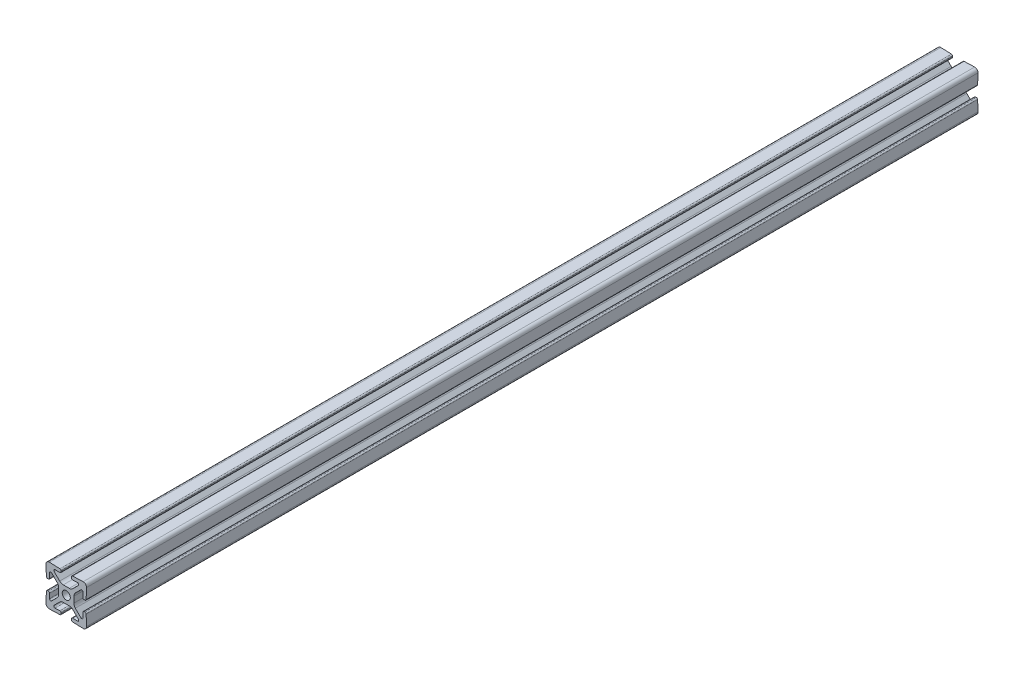
SolidWorks part; units mm, degrees
ref_plane "Front Plane" through (0, 0, 0) normal (0, 0, 1) x (1, 0, 0)
ref_plane "Top Plane" through (0, 0, 0) normal (0, 1, 0) x (1, 0, 0)
ref_plane "Right Plane" through (0, 0, 0) normal (1, 0, 0) x (0, 0, -1)
sketch "Sketch1" plane through (0, 0, 0) normal (0, 0, 1) x (1, 0, 0)
  line L0 (0, 0) -> (0, 12.7) construction
  line L1 (0, 0) -> (12.7, 0) construction
  line L2 (0, 0) -> (-12.7, 12.7) construction
  line L3 (-10.5971, 12.6988) -> (-3.9739, 12.4675)
  line L4 (-12.7, 12.7) -> (0, 12.7) construction
  line L6 (-4.0475, 10.3606) -> (-7.0332, 10.4648)
  line L10 (0, 4.7625) -> (-1.8848, 4.7625)
  line L11 (-4.1299, 5.6924) -> (-7.5996, 9.1622)
  line L24 (0, 0) -> (-12.7, 0) construction
  line L25 (-12.7, 0) -> (0, 0) construction
  line L26 (0, 0) -> (0, -12.7) construction
  line L27 (-12.7, -12.7) -> (-12.7, 12.7) construction
  line L28 (0, 12.7) -> (12.7, 12.7) construction
  line L29 (-3.239, 11.6793) -> (-3.2594, 11.0955)
  line L30 (-12.7, -12.7) -> (12.7, -12.7) construction
  arc A0 (-12.1048, 12.1048) -> (-10.5971, 12.6988) centre (-10.668, 10.668) cw
  arc A6 (-1.8848, 4.7625) -> (-4.1299, 5.6924) centre (-1.8848, 7.9375) cw
  circle A16 centre (0, 0) radius 2.54
  arc A18 (-7.5996, 9.1622) -> (-7.0332, 10.4648) centre (-7.0599, 9.702) cw
  circle A19 centre (-2.3794, 2.3794) radius 0.635 construction
  arc A20 (-4.0475, 10.3606) -> (-3.2594, 11.0955) centre (-4.0209, 11.1221) ccw
  arc A21 (-3.9739, 12.4675) -> (-3.239, 11.6793) centre (-4.0005, 11.7059) cw
  point P15 (0, 0)
  point P42 (-3.1999, 4.7625)
  point P80 (-12.7, 0)
  point P85 (0, -12.7)
  point P88 (0, -12.7)
  dimension "D11" = 2.032
  dimension "D15" = 3.175
  dimension "Center Hole Diameter" = 5.08
  dimension "D6" = 1.27
  dimension "D4" = 0.7633
  dimension "D8" = 0.762
  dimension "D12" = 0.762
  dimension "D1" = 45
  dimension "D2" = 2
  dimension "Rail Width" = 25.4
  dimension "D10" = 2.2098
  dimension "T-Slot Depth" = 7.9375
  dimension "D9" = 2.1082
  dimension "Rail Height" = 25.4
  dimension "D23" = 9.525
  dimension "D5" = 15.6464
  dimension "D3" = 4
  dimension "D7" = 5.7028
  dimension "T-Slot Width" = 6.477
sketch "Sketch2" plane through (0, 0, 0) normal (1, 0, 0) x (0, 0, -1)
  line L0 (-609.6, 0) -> (609.6, 0)
  line L2 (0, 0) -> (0, 12.7) construction
  line L3 (0, 0) -> (0, 12.7) construction
  point P0 (-571.5, 0)
  point P3 (0, 0)
  point P7 (571.5, 0)
  dimension "D1" = 38.1
  dimension "Length" = 1219.2
sketch "Sketch3" plane through (0, 0, 0) normal (0, 0, 1) x (1, 0, 0)
  line L2 (0, 4.7625) -> (-1.8848, 4.7625) construction
  line L5 (-4.1299, 5.6924) -> (-7.5996, 9.1622) construction
  line L6 (-4.0475, 10.3606) -> (-7.0332, 10.4648) construction
  line L7 (-3.239, 11.6793) -> (-3.2594, 11.0955) construction
  line L67 (-10.5971, 12.6988) -> (-3.9739, 12.4675) construction
  line L68 (0, 4.7625) -> (-1.8848, 4.7625)
  line L69 (-4.1299, 5.6924) -> (-7.5996, 9.1622)
  line L70 (-4.0475, 10.3606) -> (-7.0332, 10.4648)
  line L71 (-3.239, 11.6793) -> (-3.2594, 11.0955)
  line L72 (-10.5971, 12.6988) -> (-3.9739, 12.4675)
  line L73 (0, 0) -> (-12.7, 12.7) construction
  line L74 (0, 0) -> (-12.7, 12.7) construction
  line L75 (-12.6988, 10.5971) -> (-12.4675, 3.9739)
  line L76 (-11.6793, 3.239) -> (-11.0955, 3.2594)
  line L77 (-10.3606, 4.0475) -> (-10.4648, 7.0332)
  line L78 (-5.6924, 4.1299) -> (-9.1622, 7.5996)
  line L79 (-4.7625, 0) -> (-4.7625, 1.8848)
  line L80 (-4.7625, 0) -> (-2.54, 0)
  line L82 (0, 4.7625) -> (0, 2.54)
  arc A3 (-4.1299, 5.6924) -> (-1.8848, 4.7625) centre (-1.8848, 7.9375) ccw construction
  circle A10 centre (0, 0) radius 2.54
  arc A56 (0, 2.54) -> (-2.54, 0) centre (0, 0) ccw
  arc A57 (-7.0332, 10.4648) -> (-7.5996, 9.1622) centre (-7.0599, 9.702) ccw construction
  arc A58 (-4.0475, 10.3606) -> (-3.2594, 11.0955) centre (-4.0209, 11.1221) ccw construction
  arc A59 (-3.239, 11.6793) -> (-3.9739, 12.4675) centre (-4.0005, 11.7059) ccw construction
  arc A60 (-10.5971, 12.6988) -> (-12.1048, 12.1048) centre (-10.668, 10.668) ccw construction
  arc A61 (-4.1299, 5.6924) -> (-1.8848, 4.7625) centre (-1.8848, 7.9375) ccw
  arc A62 (-7.0332, 10.4648) -> (-7.5996, 9.1622) centre (-7.0599, 9.702) ccw
  arc A63 (-4.0475, 10.3606) -> (-3.2594, 11.0955) centre (-4.0209, 11.1221) ccw
  arc A64 (-3.239, 11.6793) -> (-3.9739, 12.4675) centre (-4.0005, 11.7059) ccw
  arc A65 (-10.5971, 12.6988) -> (-12.6988, 10.5971) centre (-10.668, 10.668) ccw
  arc A67 (-11.6793, 3.239) -> (-12.4675, 3.9739) centre (-11.7059, 4.0005) cw
  arc A68 (-10.3606, 4.0475) -> (-11.0955, 3.2594) centre (-11.1221, 4.0209) cw
  arc A69 (-10.4648, 7.0332) -> (-9.1622, 7.5996) centre (-9.702, 7.0599) cw
  arc A70 (-5.6924, 4.1299) -> (-4.7625, 1.8848) centre (-7.9375, 1.8848) cw
  dimension "D1" = 0
extrude "Boss-Extrude1" add sketch "Sketch3" along normal mid plane 1219.2
pattern_circular "CirPattern1" count 4 over 360 about axis through (0, 0, 0) along (0, 0, 1) of "Boss-Extrude1"
ref_plane "Contact Plane 1" through (0, 12.7, 0) normal (0, 1, 0) x (1, 0, 0)
ref_plane "Contact Plane 2" through (12.7, 0, 0) normal (1, 0, 0) x (0, 0, -1)
ref_plane "Contact Plane 3" through (0, -12.7, 0) normal (0, -1, 0) x (-1, 0, 0)
ref_plane "Contact Plane 4" through (-12.7, 0, 0) normal (-1, 0, 0) x (0, 0, 1)
sketch "Sketch4" plane through (0, 0, 609.6) normal (0, 0, 1) x (1, 0, 0)
  line L36 (1.8848, 4.7625) -> (-1.8848, 4.7625)
  line L37 (-4.1299, 5.6924) -> (-7.5996, 9.1622)
  line L38 (-7.0332, 10.4648) -> (-4.0475, 10.3606)
  line L39 (-3.2594, 11.0955) -> (-3.239, 11.6793)
  line L40 (-3.9739, 12.4675) -> (-10.5971, 12.6988)
  line L41 (-12.6988, 10.5971) -> (-12.4675, 3.9739)
  line L42 (-11.6793, 3.239) -> (-11.0955, 3.2594)
  line L43 (-10.3606, 4.0475) -> (-10.4648, 7.0332)
  line L44 (-9.1622, 7.5996) -> (-5.6924, 4.1299)
  line L45 (-4.7625, 1.8848) -> (-4.7625, -1.8848)
  line L46 (-5.6924, -4.1299) -> (-9.1622, -7.5996)
  line L47 (-10.4648, -7.0332) -> (-10.3606, -4.0475)
  line L48 (-11.0955, -3.2594) -> (-11.6793, -3.239)
  line L49 (-12.4675, -3.9739) -> (-12.6988, -10.5971)
  line L50 (-10.5971, -12.6988) -> (-3.9739, -12.4675)
  line L51 (-3.239, -11.6793) -> (-3.2594, -11.0955)
  line L52 (-4.0475, -10.3606) -> (-7.0332, -10.4648)
  line L53 (-7.5996, -9.1622) -> (-4.1299, -5.6924)
  line L54 (-1.8848, -4.7625) -> (1.8848, -4.7625)
  line L55 (4.1299, -5.6924) -> (7.5996, -9.1622)
  line L56 (7.0332, -10.4648) -> (4.0475, -10.3606)
  line L57 (3.2594, -11.0955) -> (3.239, -11.6793)
  line L58 (3.9739, -12.4675) -> (10.5971, -12.6988)
  line L59 (12.6988, -10.5971) -> (12.4675, -3.9739)
  line L60 (11.6793, -3.239) -> (11.0955, -3.2594)
  line L61 (10.3606, -4.0475) -> (10.4648, -7.0332)
  line L62 (9.1622, -7.5996) -> (5.6924, -4.1299)
  line L63 (4.7625, -1.8848) -> (4.7625, 1.8848)
  line L64 (5.6924, 4.1299) -> (9.1622, 7.5996)
  line L65 (10.4648, 7.0332) -> (10.3606, 4.0475)
  line L66 (11.0955, 3.2594) -> (11.6793, 3.239)
  line L67 (12.4675, 3.9739) -> (12.6988, 10.5971)
  line L68 (10.5971, 12.6988) -> (3.9739, 12.4675)
  line L69 (3.239, 11.6793) -> (3.2594, 11.0955)
  line L70 (4.0475, 10.3606) -> (7.0332, 10.4648)
  line L71 (7.5996, 9.1622) -> (4.1299, 5.6924)
  line L72 (1.8848, 4.7625) -> (-1.8848, 4.7625)
  line L73 (-4.1299, 5.6924) -> (-7.5996, 9.1622)
  line L74 (-7.0332, 10.4648) -> (-4.0475, 10.3606)
  line L75 (-3.2594, 11.0955) -> (-3.239, 11.6793)
  line L76 (-3.9739, 12.4675) -> (-10.5971, 12.6988)
  line L77 (-12.6988, 10.5971) -> (-12.4675, 3.9739)
  line L78 (-11.6793, 3.239) -> (-11.0955, 3.2594)
  line L79 (-10.3606, 4.0475) -> (-10.4648, 7.0332)
  line L80 (-9.1622, 7.5996) -> (-5.6924, 4.1299)
  line L81 (-4.7625, 1.8848) -> (-4.7625, -1.8848)
  line L82 (-5.6924, -4.1299) -> (-9.1622, -7.5996)
  line L83 (-10.4648, -7.0332) -> (-10.3606, -4.0475)
  line L84 (-11.0955, -3.2594) -> (-11.6793, -3.239)
  line L85 (-12.4675, -3.9739) -> (-12.6988, -10.5971)
  line L86 (-10.5971, -12.6988) -> (-3.9739, -12.4675)
  line L87 (-3.239, -11.6793) -> (-3.2594, -11.0955)
  line L88 (-4.0475, -10.3606) -> (-7.0332, -10.4648)
  line L89 (-7.5996, -9.1622) -> (-4.1299, -5.6924)
  line L90 (-1.8848, -4.7625) -> (1.8848, -4.7625)
  line L91 (4.1299, -5.6924) -> (7.5996, -9.1622)
  line L92 (7.0332, -10.4648) -> (4.0475, -10.3606)
  line L93 (3.2594, -11.0955) -> (3.239, -11.6793)
  line L94 (3.9739, -12.4675) -> (10.5971, -12.6988)
  line L95 (12.6988, -10.5971) -> (12.4675, -3.9739)
  line L96 (11.6793, -3.239) -> (11.0955, -3.2594)
  line L97 (10.3606, -4.0475) -> (10.4648, -7.0332)
  line L98 (9.1622, -7.5996) -> (5.6924, -4.1299)
  line L99 (4.7625, -1.8848) -> (4.7625, 1.8848)
  line L100 (5.6924, 4.1299) -> (9.1622, 7.5996)
  line L101 (10.4648, 7.0332) -> (10.3606, 4.0475)
  line L102 (11.0955, 3.2594) -> (11.6793, 3.239)
  line L103 (12.4675, 3.9739) -> (12.6988, 10.5971)
  line L104 (10.5971, 12.6988) -> (3.9739, 12.4675)
  line L105 (3.239, 11.6793) -> (3.2594, 11.0955)
  line L106 (4.0475, 10.3606) -> (7.0332, 10.4648)
  line L107 (7.5996, 9.1622) -> (4.1299, 5.6924)
  arc A36 (1.8848, 4.7625) -> (4.1299, 5.6924) centre (1.8848, 7.9375) ccw
  arc A37 (-4.1299, 5.6924) -> (-1.8848, 4.7625) centre (-1.8848, 7.9375) ccw
  arc A38 (-7.0332, 10.4648) -> (-7.5996, 9.1622) centre (-7.0599, 9.702) ccw
  arc A39 (-4.0475, 10.3606) -> (-3.2594, 11.0955) centre (-4.0209, 11.1221) ccw
  arc A40 (-3.239, 11.6793) -> (-3.9739, 12.4675) centre (-4.0005, 11.7059) ccw
  arc A41 (-10.5971, 12.6988) -> (-12.6988, 10.5971) centre (-10.668, 10.668) ccw
  arc A42 (-12.4675, 3.9739) -> (-11.6793, 3.239) centre (-11.7059, 4.0005) ccw
  arc A43 (-11.0955, 3.2594) -> (-10.3606, 4.0475) centre (-11.1221, 4.0209) ccw
  arc A44 (-9.1622, 7.5996) -> (-10.4648, 7.0332) centre (-9.702, 7.0599) ccw
  arc A45 (-4.7625, 1.8848) -> (-5.6924, 4.1299) centre (-7.9375, 1.8848) ccw
  arc A46 (-5.6924, -4.1299) -> (-4.7625, -1.8848) centre (-7.9375, -1.8848) ccw
  arc A47 (-10.4648, -7.0332) -> (-9.1622, -7.5996) centre (-9.702, -7.0599) ccw
  arc A48 (-10.3606, -4.0475) -> (-11.0955, -3.2594) centre (-11.1221, -4.0209) ccw
  arc A49 (-11.6793, -3.239) -> (-12.4675, -3.9739) centre (-11.7059, -4.0005) ccw
  arc A50 (-12.6988, -10.5971) -> (-10.5971, -12.6988) centre (-10.668, -10.668) ccw
  arc A51 (-3.9739, -12.4675) -> (-3.239, -11.6793) centre (-4.0005, -11.7059) ccw
  arc A52 (-3.2594, -11.0955) -> (-4.0475, -10.3606) centre (-4.0209, -11.1221) ccw
  arc A53 (-7.5996, -9.1622) -> (-7.0332, -10.4648) centre (-7.0599, -9.702) ccw
  arc A54 (-1.8848, -4.7625) -> (-4.1299, -5.6924) centre (-1.8848, -7.9375) ccw
  arc A55 (4.1299, -5.6924) -> (1.8848, -4.7625) centre (1.8848, -7.9375) ccw
  arc A56 (7.0332, -10.4648) -> (7.5996, -9.1622) centre (7.0599, -9.702) ccw
  arc A57 (4.0475, -10.3606) -> (3.2594, -11.0955) centre (4.0209, -11.1221) ccw
  arc A58 (3.239, -11.6793) -> (3.9739, -12.4675) centre (4.0005, -11.7059) ccw
  arc A59 (10.5971, -12.6988) -> (12.6988, -10.5971) centre (10.668, -10.668) ccw
  arc A60 (12.4675, -3.9739) -> (11.6793, -3.239) centre (11.7059, -4.0005) ccw
  arc A61 (11.0955, -3.2594) -> (10.3606, -4.0475) centre (11.1221, -4.0209) ccw
  arc A62 (9.1622, -7.5996) -> (10.4648, -7.0332) centre (9.702, -7.0599) ccw
  arc A63 (4.7625, -1.8848) -> (5.6924, -4.1299) centre (7.9375, -1.8848) ccw
  arc A64 (5.6924, 4.1299) -> (4.7625, 1.8848) centre (7.9375, 1.8848) ccw
  arc A65 (10.4648, 7.0332) -> (9.1622, 7.5996) centre (9.702, 7.0599) ccw
  arc A66 (10.3606, 4.0475) -> (11.0955, 3.2594) centre (11.1221, 4.0209) ccw
  arc A67 (11.6793, 3.239) -> (12.4675, 3.9739) centre (11.7059, 4.0005) ccw
  arc A68 (12.6988, 10.5971) -> (10.5971, 12.6988) centre (10.668, 10.668) ccw
  arc A69 (3.9739, 12.4675) -> (3.239, 11.6793) centre (4.0005, 11.7059) ccw
  arc A70 (3.2594, 11.0955) -> (4.0475, 10.3606) centre (4.0209, 11.1221) ccw
  arc A71 (7.5996, 9.1622) -> (7.0332, 10.4648) centre (7.0599, 9.702) ccw
  arc A72 (1.8848, 4.7625) -> (4.1299, 5.6924) centre (1.8848, 7.9375) ccw
  arc A73 (-4.1299, 5.6924) -> (-1.8848, 4.7625) centre (-1.8848, 7.9375) ccw
  arc A74 (-7.0332, 10.4648) -> (-7.5996, 9.1622) centre (-7.0599, 9.702) ccw
  arc A75 (-4.0475, 10.3606) -> (-3.2594, 11.0955) centre (-4.0209, 11.1221) ccw
  arc A76 (-3.239, 11.6793) -> (-3.9739, 12.4675) centre (-4.0005, 11.7059) ccw
  arc A77 (-10.5971, 12.6988) -> (-12.6988, 10.5971) centre (-10.668, 10.668) ccw
  arc A78 (-12.4675, 3.9739) -> (-11.6793, 3.239) centre (-11.7059, 4.0005) ccw
  arc A79 (-11.0955, 3.2594) -> (-10.3606, 4.0475) centre (-11.1221, 4.0209) ccw
  arc A80 (-9.1622, 7.5996) -> (-10.4648, 7.0332) centre (-9.702, 7.0599) ccw
  arc A81 (-4.7625, 1.8848) -> (-5.6924, 4.1299) centre (-7.9375, 1.8848) ccw
  arc A82 (-5.6924, -4.1299) -> (-4.7625, -1.8848) centre (-7.9375, -1.8848) ccw
  arc A83 (-10.4648, -7.0332) -> (-9.1622, -7.5996) centre (-9.702, -7.0599) ccw
  arc A84 (-10.3606, -4.0475) -> (-11.0955, -3.2594) centre (-11.1221, -4.0209) ccw
  arc A85 (-11.6793, -3.239) -> (-12.4675, -3.9739) centre (-11.7059, -4.0005) ccw
  arc A86 (-12.6988, -10.5971) -> (-10.5971, -12.6988) centre (-10.668, -10.668) ccw
  arc A87 (-3.9739, -12.4675) -> (-3.239, -11.6793) centre (-4.0005, -11.7059) ccw
  arc A88 (-3.2594, -11.0955) -> (-4.0475, -10.3606) centre (-4.0209, -11.1221) ccw
  arc A89 (-7.5996, -9.1622) -> (-7.0332, -10.4648) centre (-7.0599, -9.702) ccw
  arc A90 (-1.8848, -4.7625) -> (-4.1299, -5.6924) centre (-1.8848, -7.9375) ccw
  arc A91 (4.1299, -5.6924) -> (1.8848, -4.7625) centre (1.8848, -7.9375) ccw
  arc A92 (7.0332, -10.4648) -> (7.5996, -9.1622) centre (7.0599, -9.702) ccw
  arc A93 (4.0475, -10.3606) -> (3.2594, -11.0955) centre (4.0209, -11.1221) ccw
  arc A94 (3.239, -11.6793) -> (3.9739, -12.4675) centre (4.0005, -11.7059) ccw
  arc A95 (10.5971, -12.6988) -> (12.6988, -10.5971) centre (10.668, -10.668) ccw
  arc A96 (12.4675, -3.9739) -> (11.6793, -3.239) centre (11.7059, -4.0005) ccw
  arc A97 (11.0955, -3.2594) -> (10.3606, -4.0475) centre (11.1221, -4.0209) ccw
  arc A98 (9.1622, -7.5996) -> (10.4648, -7.0332) centre (9.702, -7.0599) ccw
  arc A99 (4.7625, -1.8848) -> (5.6924, -4.1299) centre (7.9375, -1.8848) ccw
  arc A100 (5.6924, 4.1299) -> (4.7625, 1.8848) centre (7.9375, 1.8848) ccw
  arc A101 (10.4648, 7.0332) -> (9.1622, 7.5996) centre (9.702, 7.0599) ccw
  arc A102 (10.3606, 4.0475) -> (11.0955, 3.2594) centre (11.1221, 4.0209) ccw
  arc A103 (11.6793, 3.239) -> (12.4675, 3.9739) centre (11.7059, 4.0005) ccw
  arc A104 (12.6988, 10.5971) -> (10.5971, 12.6988) centre (10.668, 10.668) ccw
  arc A105 (3.9739, 12.4675) -> (3.239, 11.6793) centre (4.0005, 11.7059) ccw
  arc A106 (3.2594, 11.0955) -> (4.0475, 10.3606) centre (4.0209, 11.1221) ccw
  arc A107 (7.5996, 9.1622) -> (7.0332, 10.4648) centre (7.0599, 9.702) ccw
  dimension "D1" = 0
extrude "Cut-Extrude1" cut sketch "Sketch4" against normal offset from surface (660.4 mm away) 558.8 up to face at (0, 0, -609.6)
equation "\"D1@Sketch2\"=\"Rail Width@Sketch1\"*1.5"
equation "\"D1@Boss-Extrude1\"=\"Length@Sketch2\""
